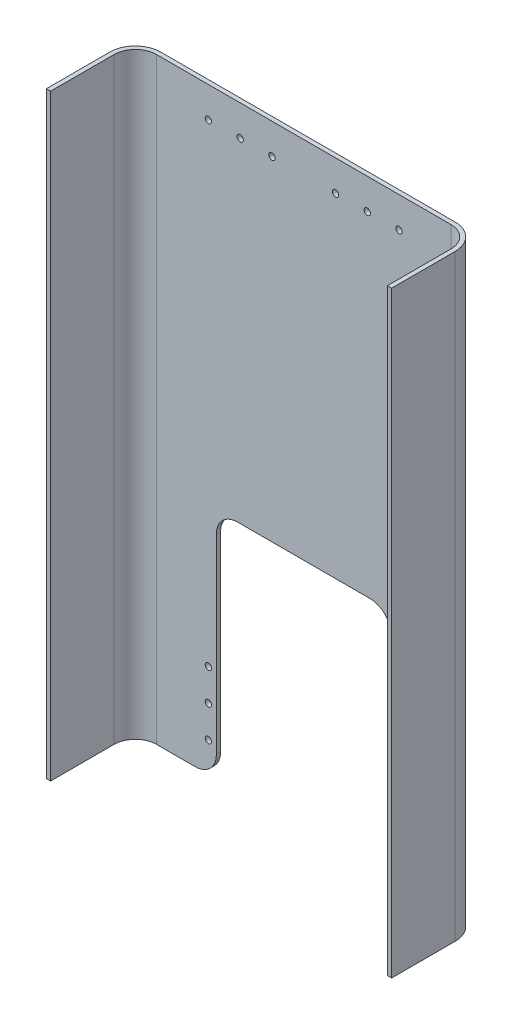
SolidWorks part; units mm, degrees
material "Polycarbonate, Black"
ref_plane "Front Plane" through (0, 0, 0) normal (0, 0, 1) x (1, 0, 0)
ref_plane "Top Plane" through (0, 0, 0) normal (0, 1, 0) x (1, 0, 0)
ref_plane "Right Plane" through (0, 0, 0) normal (1, 0, 0) x (0, 0, -1)
sketch "Sketch1" plane through (0, 0, 0) normal (0, 1, 0) x (1, 0, 0)
  line L0 (-159, -80) -> (-159, -20)
  line L1 (-139, 0) -> (139, 0)
  line L2 (159, -20) -> (159, -80)
  arc A0 (139, 0) -> (159, -20) centre (139, -20) cw
  arc A1 (-159, -20) -> (-139, 0) centre (-139, -20) cw
  dimension "D1" = 20
  dimension "D2" = 318
  dimension "D3" = 80
extrude "Extrude-Thin1" add sketch "Sketch1" along normal blind 564 thin thin type one direction reverse wall 4
sketch "Sketch2" plane through (0, 0, -4) normal (0, 0, -1) x (-1, 0, 0)
  line L0 (139, 0) -> (-139, 0) construction
  line L1 (-82.5, -85.2671) -> (82.5, -85.2671)
  line L2 (-82.5, -85.2671) -> (-82.5, 175)
  line L3 (-82.5, 175) -> (82.5, 175)
  line L4 (82.5, -85.2671) -> (82.5, 175)
  line L5 (0, 0) -> (0, 175) construction
  dimension "D1" = 175
  dimension "D2" = 165
extrude "Cut-Extrude1" [suppressed] cut sketch "Sketch2" against normal through all both and the other way through all
sketch "Sketch3" plane through (0, 0, -4) normal (0, 0, -1) x (-1, 0, 0)
  line L0 (139, 0) -> (-139, 0) construction
  line L1 (-82.5, 0) -> (82.5, 0)
  line L2 (-82.5, 0) -> (-82.5, 220)
  line L3 (-82.5, 220) -> (82.5, 220)
  line L4 (82.5, 0) -> (82.5, 220)
  dimension "D1" = 165
  dimension "D2" = 220
extrude "Cut-Extrude2" cut sketch "Sketch3" against normal through all both and the other way through all
fillet "Fillet1" radius 20 4 edges at (82.5, 220, -2) (-82.5, 220, -2) (-82.5, 0, -2) (82.5, 0, -2)
fillet "Fillet2" [suppressed] radius 10
fillet "Fillet3" [suppressed] radius 20
sketch "Sketch4" plane through (0, 0, -4) normal (0, 0, -1) x (-1, 0, 0)
  line L0 (-90, 535) -> (-60, 535) construction
  line L1 (-60, 535) -> (-30, 535) construction
  line L2 (-90, 28.126) -> (-90, 58.126) construction
  line L3 (-90, 58.126) -> (-90, 88.126) construction
  circle A0 centre (-90, 535) radius 3
  circle A1 centre (-60, 535) radius 3
  circle A2 centre (-30, 535) radius 3
  circle A5 centre (-90, 88.126) radius 3
  circle A6 centre (-90, 58.126) radius 3
  circle A7 centre (-90, 28.126) radius 3
  point P13 (0, 0)
  point P14 (0, 0)
  dimension "D2" = 6
  dimension "D5" = 6
  dimension "D1" = 535
  dimension "D3" = 30
  dimension "D4" = 30
  dimension "D6" = 30
  dimension "D7" = 90
  dimension "D8" = 88.126
extrude "Cut-Extrude3" cut sketch "Sketch4" against normal through all
mirror "Mirror1" about plane through (0, 0, 0) normal (1, 0, 0) of "Cut-Extrude3"
